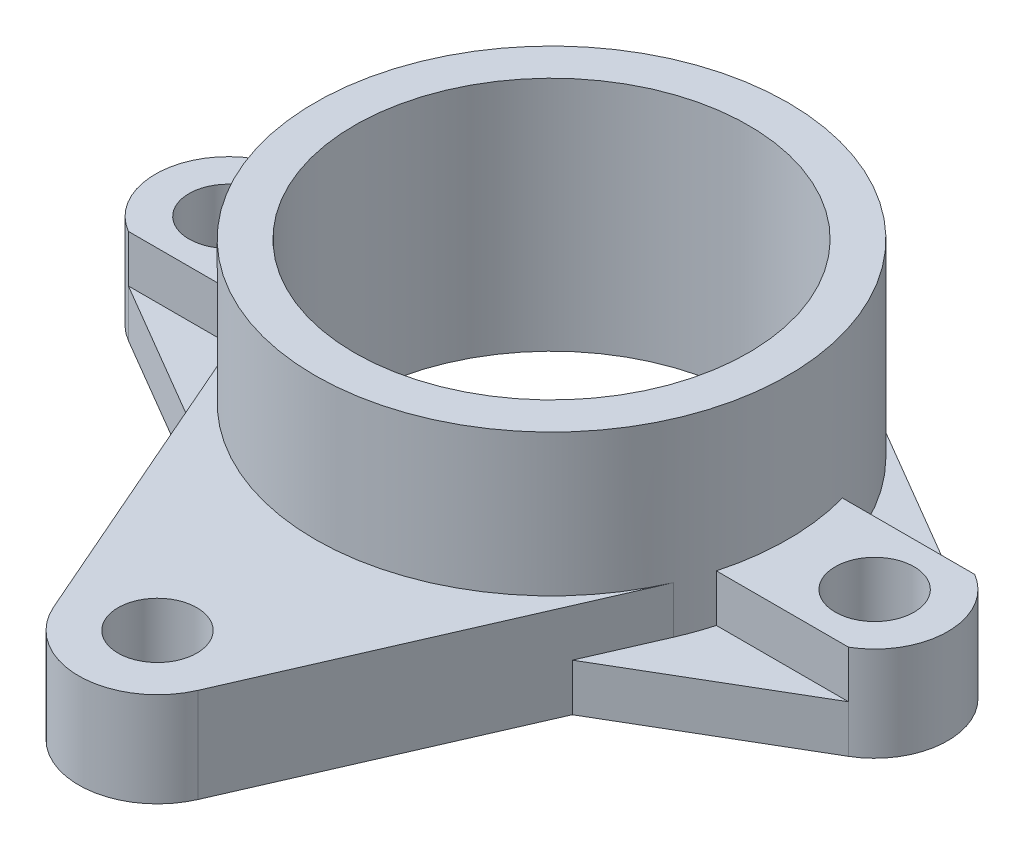
SolidWorks part; units mm, degrees
ref_plane "Front Plane" through (0, 0, 0) normal (0, 0, 1) x (1, 0, 0)
ref_plane "Top Plane" through (0, 0, 0) normal (0, 1, 0) x (1, 0, 0)
ref_plane "Right Plane" through (0, 0, 0) normal (1, 0, 0) x (0, 0, -1)
ref_plane "Plane1" through (0, 12, 0) normal (0, 1, 0) x (1, 0, 0)
sketch "Sketch1" plane through (0, 12, 0) normal (0, 1, 0) x (1, 0, 0)
  line L0 (-45.6876, -8) -> (-28.9137, -8)
  line L1 (-27.4955, -12) -> (-9.1652, -54)
  line L2 (9.1652, -54) -> (27.4955, -12)
  line L3 (28.9137, -8) -> (45.6876, -8)
  line L4 (45.6876, 8) -> (28.9137, 8)
  line L5 (-28.9137, 8) -> (-45.6876, 8)
  arc A0 (-45.6876, 8) -> (-45.6876, -8) centre (-41, 0) ccw
  arc A1 (-28.9137, -8) -> (-27.4955, -12) centre (0, 0) ccw
  arc A2 (-9.1652, -54) -> (9.1652, -54) centre (0, -50) ccw
  arc A3 (27.4955, -12) -> (28.9137, -8) centre (0, 0) ccw
  arc A4 (45.6876, -8) -> (45.6876, 8) centre (41, 0) ccw
  arc A5 (28.9137, 8) -> (-28.9137, 8) centre (0, 0) ccw
extrude "Boss-Extrude1" add sketch "Sketch1" against normal blind 6
sketch "Sketch2" plane through (0, 6, 0) normal (0, -1, 0) x (1, 0, 0)
  line L0 (-15.1667, -25.8838) -> (-45.6876, -8)
  line L1 (-45.6876, 8) -> (-23.5902, 20.948)
  line L2 (-23.5902, 20.948) -> (-9.1652, 54)
  line L3 (9.1652, 54) -> (23.5902, 20.948)
  line L4 (23.5902, 20.948) -> (45.6876, 8)
  line L5 (45.6876, -8) -> (15.1667, -25.8838)
  line L6 (-28.9137, -8) -> (-45.6876, -8) construction
  arc A0 (15.1667, -25.8838) -> (-15.1667, -25.8838) centre (0, 0) cw
  arc A1 (-45.6876, -8) -> (-45.6876, 8) centre (-41, 0) cw
  arc A2 (-9.1652, 54) -> (9.1652, 54) centre (0, 50) cw
  arc A3 (45.6876, 8) -> (45.6876, -8) centre (41, 0) cw
extrude "Boss-Extrude2" add sketch "Sketch2" along normal blind 6
sketch "Sketch3" plane through (0, 12, 0) normal (0, 1, 0) x (-1, 0, 0)
  circle A0 centre (0, 0) radius 30
extrude "Boss-Extrude3" add sketch "Sketch3" along normal blind 18
hole_wizard "Ø10.0 (10) Diameter Hole1" positions "Sketch5" profile "Sketch4" hole size "Ø10.0" standard "ANSI Metric"
sketch "Sketch5" plane through (0, 12, 0) normal (0, 1, 0) x (1, 0, 0)
  point P0 (-41, 0)
  point P1 (41, 0)
  point P2 (0, -50)
sketch "Sketch4" plane through (-41, 12, 0) normal (1, 0, 0) x (0, 0, 1)
  line L0 (0, 0) -> (0, 12)
  line L1 (0, 12) -> (5, 12)
  line L2 (5, 12) -> (5, 0)
  line L5 (5, 0) -> (0, 0)
  line L11 (0, -6.35) -> (0, 107.95) construction
  dimension "Thru Hole Dia." = 10
  dimension "Thru Hole Depth" = 12
hole_wizard "M45 Clearance Hole1" positions "Sketch7" profile "Sketch6" hole size "M45" standard "ANSI Metric"
sketch "Sketch7" plane through (0, 30, 0) normal (0, 1, 0) x (1, 0, 0)
  point P0 (0, 0)
sketch "Sketch6" plane through (0, 30, 0) normal (1, 0, 0) x (0, 0, 1)
  line L0 (0, 0) -> (0, 30)
  line L1 (0, 30) -> (25, 30)
  line L2 (25, 30) -> (25, 0)
  line L5 (25, 0) -> (0, 0)
  line L11 (0, -6.35) -> (0, 107.95) construction
  dimension "Thru Hole Dia." = 50
  dimension "Thru Hole Depth" = 30
